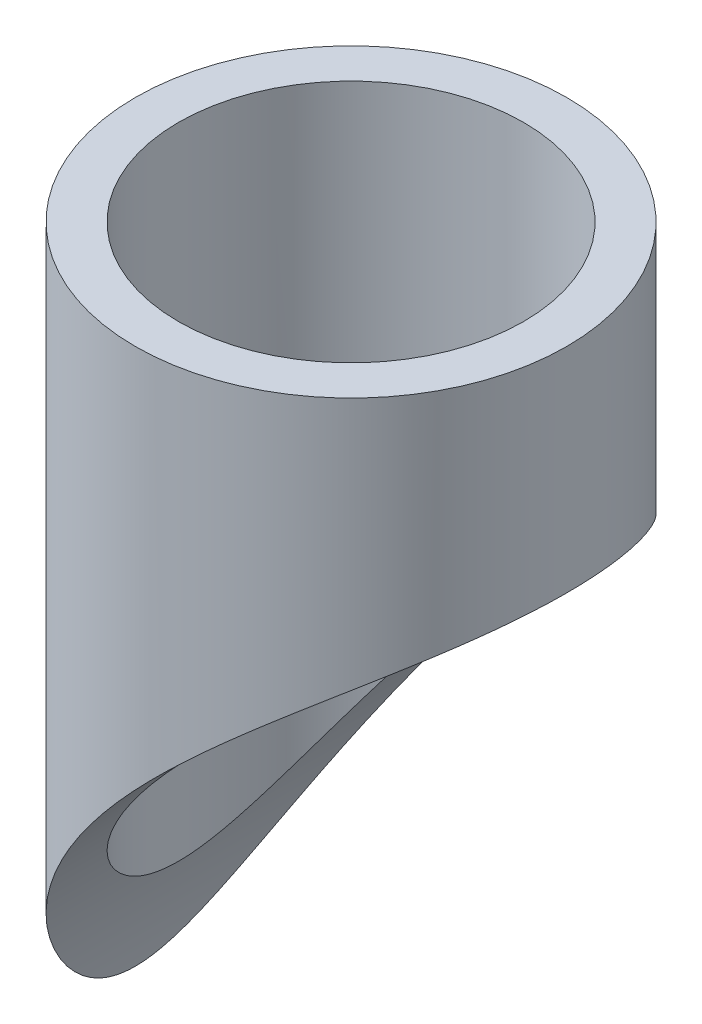
SolidWorks part; units mm, degrees
ref_plane "Front Plane" through (0, 0, 0) normal (0, 0, 1) x (1, 0, 0)
ref_plane "Top Plane" through (0, 0, 0) normal (0, 1, 0) x (1, 0, 0)
ref_plane "Right Plane" through (0, 0, 0) normal (1, 0, 0) x (0, 0, -1)
sketch "Sketch1" plane through (0, 0, 0) normal (0, 1, 0) x (1, 0, 0)
  circle A0 centre (0, 0) radius 12.7
  circle A1 centre (0, 0) radius 15.875
  dimension "D1" = 25.4
  dimension "D2" = 3.175
extrude "Boss-Extrude1" add sketch "Sketch1" along normal blind 76.2
sketch "Sketch2" plane through (0, 0, 0) normal (0, 0, 1) x (1, 0, 0)
  circle A0 centre (50.8, 0) radius 69.85
  circle A1 centre (50.8, 0) radius 63.5
  point P2 (75.269, 0)
  point P3 (50.8, 0)
  dimension "D1" = 139.7
  dimension "D2" = 127
extrude "Cut-Extrude1" cut sketch "Sketch2" against normal through all both and the other way through all contours A1 | A0 A1
